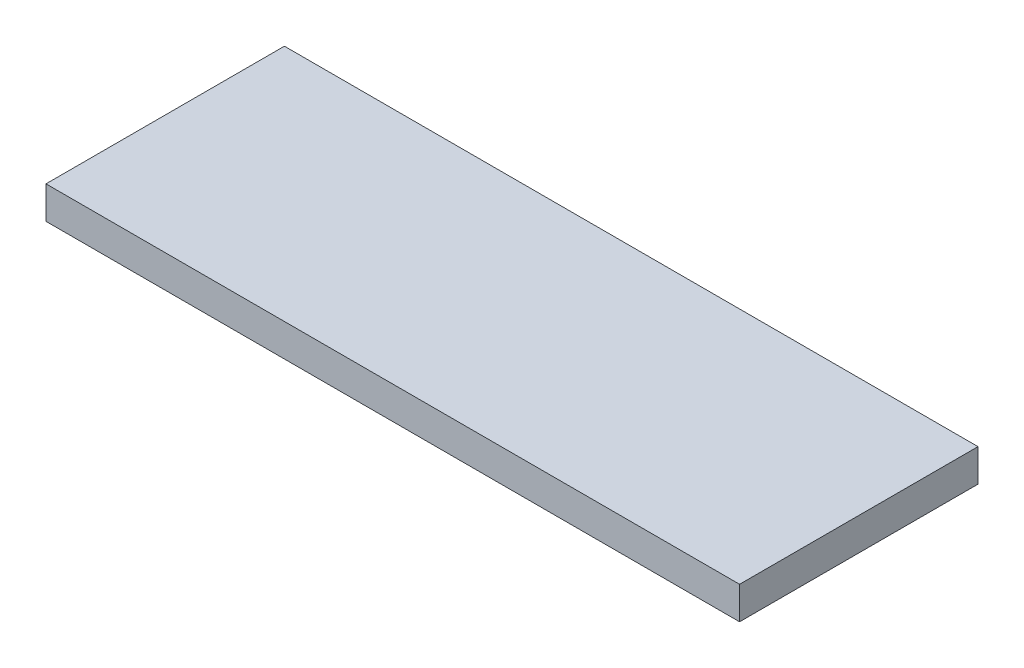
SolidWorks part; units mm, degrees
ref_plane "Front" through (0, 0, 0) normal (0, 0, 1) x (1, 0, 0)
ref_plane "Top" through (0, 0, 0) normal (0, 1, 0) x (1, 0, 0)
ref_plane "Right" through (0, 0, 0) normal (1, 0, 0) x (0, 0, -1)
sketch "Sketch1" plane through (0, 0, 0) normal (0, 1, 0) x (1, 0, 0)
  line L1 (-80, 27.5) -> (80, 27.5)
  line L2 (-80, 27.5) -> (-80, -27.5)
  line L3 (-80, -27.5) -> (80, -27.5)
  line L4 (80, 27.5) -> (80, -27.5)
  line L5 (-80, 27.5) -> (80, -27.5) construction
  line L6 (-80, -27.5) -> (80, 27.5) construction
  point P0 (0, 0)
  dimension "D1" = 160
  dimension "D2" = 55
extrude "Boss-Extrude1" add sketch "Sketch1" along normal mid plane 7.5
sketch "Sketch2" plane through (0, -3.75, 0) normal (0, -1, 0) x (1, 0, 0)
  line L0 (64.1682, 22.5) -> (74.1682, 22.5) construction
  line L1 (76.1682, 24.5) -> (62.1682, 24.5)
  line L2 (76.1682, 24.5) -> (76.1682, 10.5)
  line L3 (76.1682, 10.5) -> (62.1682, 10.5)
  line L4 (62.1682, 24.5) -> (62.1682, 10.5)
  line L9 (64.1682, 12.5) -> (74.1682, 12.5) construction
  line L10 (74.1682, 22.5) -> (74.1682, 12.5) construction
  line L11 (64.1682, 12.5) -> (64.1682, 22.5) construction
  line L12 (50, 0) -> (-50, 0) construction
  line L13 (62.1682, -24.5) -> (62.1682, -10.5)
  line L14 (76.1682, -10.5) -> (62.1682, -10.5)
  line L15 (76.1682, -24.5) -> (76.1682, -10.5)
  line L16 (76.1682, -24.5) -> (62.1682, -24.5)
  line L17 (-41.1682, -9.5) -> (-31.1682, -9.5)
  line L18 (-31.1682, -9.5) -> (-31.1682, -25.5)
  line L19 (-31.1682, -25.5) -> (-77.1682, -25.5)
  line L20 (-77.1682, -25.5) -> (-77.1682, 25.5)
  line L21 (-77.1682, 25.5) -> (-31.1682, 25.5)
  line L22 (-31.1682, 25.5) -> (-31.1682, 9.5)
  line L23 (-31.1682, 9.5) -> (-41.1682, 9.5)
  line L24 (-41.1682, 9.5) -> (-41.1682, -9.5)
  line L25 (-74.1682, 75) -> (-74.1682, -75) construction
  line L26 (-44.1682, 22.5) -> (-74.1682, 22.5) construction
  line L27 (-34.1682, 22.5) -> (-34.1682, 12.5) construction
  line L28 (-44.1682, -75) -> (-44.1682, 75) construction
  line L29 (-41.6682, 12.5) -> (-44.1682, 12.5) construction
  line L30 (-44.1682, -12.5) -> (-41.6682, -12.5) construction
  line L31 (-34.1682, -22.5) -> (-44.1682, -22.5) construction
  line L32 (-34.1682, -12.5) -> (-34.1682, -22.5) construction
  dimension "D1" = 2
  dimension "D2" = 2
  dimension "D3" = 2
  dimension "D4" = 2
  dimension "D5" = 3
  dimension "D6" = 3
  dimension "D7" = 3
  dimension "D8" = 3
  dimension "D9" = 3
  dimension "D10" = 3
  dimension "D11" = 3
  dimension "D12" = 3
extrude "Cut-Extrude1" cut sketch "Sketch2" against normal blind 3.5
